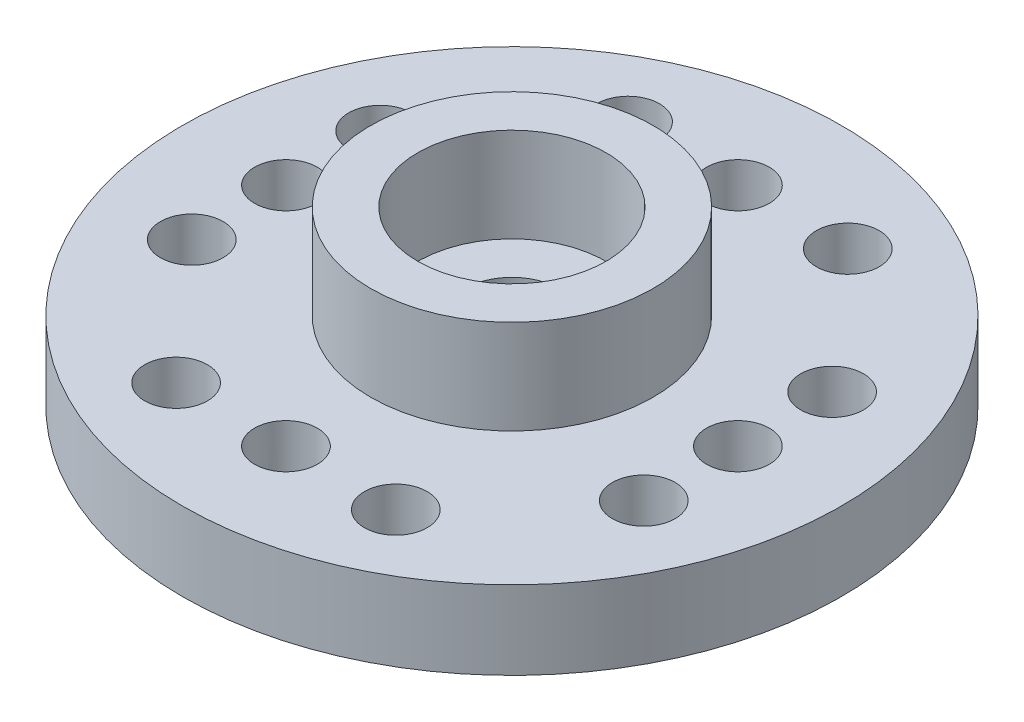
SolidWorks part; units mm, degrees
ref_plane "Alzado" through (0, 0, 0) normal (0, 0, 1) x (1, 0, 0)
ref_plane "Planta" through (0, 0, 0) normal (0, 1, 0) x (1, 0, 0)
ref_plane "Vista lateral" through (0, 0, 0) normal (1, 0, 0) x (0, 0, -1)
sketch "Croquis1" plane through (0, 0, 0) normal (0, 1, 0) x (1, 0, 0)
  circle A0 centre (0, 0) radius 10.5
  dimension "D1" = 21
extrude "Saliente-Extruir1" add sketch "Croquis1" along normal blind 2.5
sketch "Croquis2" plane through (0, 2.5, 0) normal (0, 1, 0) x (1, 0, 0)
  circle A0 centre (0, 0) radius 4.5
  circle A1 centre (0, 0) radius 3
  dimension "D1" = 9
  dimension "D2" = 6
extrude "Saliente-Extruir2" add sketch "Croquis2" along normal blind 3
sketch "Croquis4" plane through (0, 0, 0) normal (0, -1, 0) x (1, 0, 0)
  circle A1 centre (0, 0) radius 3.25
  circle A2 centre (0, 0) radius 4.75
  dimension "D2" = 9.5
  dimension "D3" = 6.5
extrude "Cortar-Extruir1" cut sketch "Croquis4" against normal blind 1
sketch "Croquis5" plane through (0, 0, 0) normal (0, -1, 0) x (1, 0, 0)
  circle A0 centre (0, 0) radius 3
  dimension "D1" = 6
extrude "Cortar-Extruir2" cut sketch "Croquis5" against normal blind 1
sketch "Croquis6" plane through (0, 1, 0) normal (0, -1, 0) x (1, 0, 0)
  circle A0 centre (0, 0) radius 1.5
  dimension "D1" = 3
extrude "Cortar-Extruir3" cut sketch "Croquis6" against normal blind 3
sketch "Croquis7" plane through (0, 0, 0) normal (0, -1, 0) x (1, 0, 0)
  line L0 (0, 10.5) -> (0, 4.75) construction
  line L1 (0, 4.75) -> (0, 0) construction
  line L2 (0, 0) -> (10.5, 0) construction
  circle A0 centre (0, 7.2) radius 1
  circle A1 centre (0, -7.2) radius 1
  circle A2 centre (0, 0) radius 10.5 construction
  circle A3 centre (0, 0) radius 4.75 construction
  circle A4 centre (0, 0) radius 4.75 construction
  circle A5 centre (7.2, 0) radius 1
  circle A6 centre (-7.2, 0) radius 1
  circle A7 centre (3.5, 7.2) radius 1
  circle A8 centre (-3.5, 7.2) radius 1
  circle A9 centre (3.5, -7.2) radius 1
  circle A10 centre (-3.5, -7.2) radius 1
  circle A11 centre (7.2, 3) radius 1
  circle A12 centre (7.2, -3) radius 1
  circle A13 centre (-7.2, -3) radius 1
  circle A14 centre (-7.2, 3) radius 1
  dimension "D2" = 2
  dimension "D4" = 2
  dimension "D7" = 2
  dimension "D8" = 2
  dimension "D9" = 2
  dimension "D10" = 2
  dimension "D1" = 7.2
  dimension "D3" = 7.2
  dimension "D5" = 3.5
  dimension "D6" = 3.5
  dimension "D11" = 3
  dimension "D12" = 3
extrude "Cortar-Extruir4" cut sketch "Croquis7" against normal blind 3
